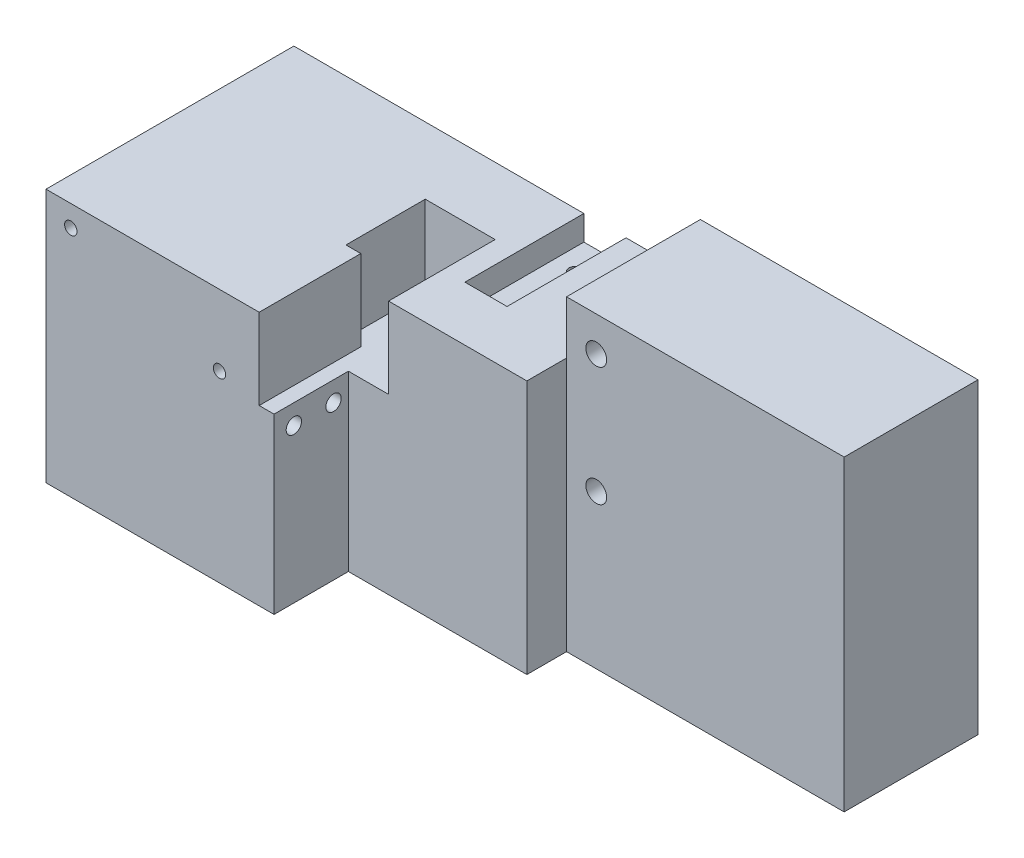
SolidWorks part; units mm, degrees
material "MC nylon"
ref_plane "Front Plane" through (0, 0, 0) normal (0, 0, 1) x (1, 0, 0)
ref_plane "Top Plane" through (0, 0, 0) normal (0, 1, 0) x (1, 0, 0)
ref_plane "Right Plane" through (0, 0, 0) normal (1, 0, 0) x (0, 0, -1)
sketch "Sketch1" plane through (0, 0, 0) normal (0, 1, 0) x (1, 0, 0)
  line L1 (0, 0) -> (138, 0)
  line L2 (0, 0) -> (0, 50)
  line L3 (0, 50) -> (138, 50)
  line L4 (138, 0) -> (138, 50)
  dimension "D1" = 50
  dimension "D2" = 138
extrude "Boss-Extrude1" add sketch "Sketch1" against normal blind 62
sketch "Sketch2" plane through (0, 0, 0) normal (0, 0, 1) x (1, 0, 0)
  line L0 (0, -62) -> (0, 0) construction
  line L1 (0, 0) -> (82, 0)
  line L2 (0, 0) -> (0, -8)
  line L3 (0, -8) -> (82, -8)
  line L4 (82, 0) -> (82, -8)
  dimension "D1" = 82
  dimension "D2" = 8
extrude "Cut-Extrude1" cut sketch "Sketch2" against normal through all
sketch "Sketch3" plane through (0, 0, 0) normal (0, 0, 1) x (1, 0, 0)
  line L1 (138, -62) -> (82, -62)
  line L2 (138, -62) -> (138, 0)
  line L3 (138, 0) -> (82, 0)
  line L4 (82, -62) -> (82, 0)
extrude "Cut-Extrude2" cut sketch "Sketch3" against normal blind 23
sketch "Sketch4" plane through (0, -8, 0) normal (0, 1, 0) x (1, 0, 0)
  line L1 (40, 36.5) -> (54.1, 36.5)
  line L2 (40, 36.5) -> (40, 20.5)
  line L3 (43, 0) -> (54.1, 0)
  line L4 (54.1, 36.5) -> (54.1, 0)
  line L9 (0, 0) -> (82, 0) construction
  line L10 (0, 50) -> (0, 0) construction
  line L11 (40, 20.5) -> (43, 20.5)
  line L14 (43, 20.5) -> (43, 0)
  dimension "D1" = 40
  dimension "D2" = 36.5
  dimension "D3" = 14.1
  dimension "D4" = 11.1
  dimension "D5" = 20.5
extrude "Cut-Extrude3" cut sketch "Sketch4" against normal blind 19
sketch "Sketch5" plane through (0, -8, 0) normal (0, 1, 0) x (1, 0, 0)
  line L6 (0, 50) -> (82, 50) construction
  line L7 (82, 0) -> (46, 0)
  line L8 (82, 0) -> (82, 15)
  line L9 (82, 15) -> (46, 15)
  line L10 (46, 0) -> (46, 15)
  dimension "D1" = 35
  dimension "D2" = 36
extrude "Cut-Extrude4" cut sketch "Sketch5" against normal through all
hole_wizard "M3x0.5 Tapped Hole1" positions "Sketch9" profile "Sketch10" tap size "M3x0.5" standard "JIS"
sketch "Sketch9" plane through (0, 0, 0) normal (0, 0, 1) x (1, 0, 0)
  line L0 (0, -8) -> (43, -8) construction
  line L1 (0, -62) -> (0, -8) construction
  point P0 (5, -15)
  point P2 (35, -25)
  dimension "D1" = 7
  dimension "D2" = 5
  dimension "D3" = 30
  dimension "D4" = 10
sketch "Sketch10" plane through (5, -15, 0) normal (1, 0, 0) x (0, -1, 0)
  line L0 (0, 0) -> (0, 13.1511)
  line L1 (0, 13.1511) -> (1.25, 12.4)
  line L2 (1.25, 12.4) -> (1.25, 0)
  line L5 (1.25, 0) -> (0, 0)
  line L10 (0, 13.1511) -> (-1.25, 12.4) construction
  line L11 (0, -6.35) -> (0, 107.95) construction
  dimension "Tap Drill Dia." = 2.5
  dimension "Tap Drill Depth" = 12.4
  dimension "Drill Angle" = 118
cosmetic thread "Hole Thread1" parameters "D1"=6, "D2"=3
cosmetic thread "Hole Thread2" parameters "D1"=6, "D2"=3
hole_wizard "M4x0.7 Tapped Hole1" positions "Sketch11" profile "Sketch12" tap size "M4x0.7" standard "JIS"
sketch "Sketch11" plane through (0, -62, 0) normal (0, -1, 0) x (-1, 0, 0)
  line L0 (-138, 23) -> (-138, 50) construction
  line L1 (0, 50) -> (0, 0) construction
  line L2 (-138, 50) -> (0, 50) construction
  point P0 (-128, 35)
  point P2 (-10, 35)
  dimension "D1" = 10
  dimension "D2" = 10
  dimension "D3" = 15
sketch "Sketch12" plane through (128, -62, -35) normal (1, 0, 0) x (0, 0, -1)
  line L0 (0, 0) -> (0, 11.0914)
  line L1 (0, 11.0914) -> (1.65, 10.1)
  line L2 (1.65, 10.1) -> (1.65, 0)
  line L5 (1.65, 0) -> (0, 0)
  line L10 (0, 11.0914) -> (-1.65, 10.1) construction
  line L11 (0, -6.35) -> (0, 107.95) construction
  dimension "Tap Drill Dia." = 3.3
  dimension "Tap Drill Depth" = 10.1
  dimension "Drill Angle" = 118
cosmetic thread "Hole Thread3" parameters "D1"=8, "D2"=4
cosmetic thread "Hole Thread4" parameters "D1"=8, "D2"=4
hole_wizard "Ø3.1 (3.1) Diameter Hole1" positions "Sketch13" profile "Sketch14" hole size "Ø3.1" standard "JIS"
sketch "Sketch13" plane through (46, 0, 0) normal (1, 0, 0) x (0, 0, -1)
  line L0 (0, -62) -> (0, -27) construction
  line L1 (15, -62) -> (0, -62) construction
  point P0 (4, -31)
  point P2 (12, -31)
  dimension "D1" = 8
  dimension "D2" = 4
  dimension "D3" = 31
sketch "Sketch14" plane through (46, -31, -4) normal (0, 1, 0) x (0, 0, -1)
  line L0 (0, 0) -> (0, 10.9313)
  line L1 (0, 10.9313) -> (1.55, 10)
  line L2 (1.55, 10) -> (1.55, 0)
  line L5 (1.55, 0) -> (0, 0)
  line L10 (0, 10.9313) -> (-1.55, 10) construction
  line L11 (0, -6.35) -> (0, 107.95) construction
  dimension "Hole Dia." = 3.1
  dimension "Hole Depth" = 10
  dimension "Drill Angle" = 118
sketch "Sketch15" plane through (0, 0, 0) normal (0, 0, 1) x (1, 0, 0)
  line L0 (82, -62) -> (82, -8) construction
  line L1 (0, -8) -> (82, -8)
  line L2 (0, -8) -> (0, -10.7)
  line L3 (0, -10.7) -> (82, -10.7)
  line L4 (82, -8) -> (82, -10.7)
  dimension "D1" = 2.7
extrude "Cut-Extrude6" cut sketch "Sketch15" against normal through all
sketch "Sketch16" plane through (0, -10.7, 0) normal (0, 1, 0) x (1, 0, 0)
  line L0 (0, 50) -> (82, 50) construction
  line L1 (58.5, 50) -> (67, 50)
  line L2 (58.5, 50) -> (58.5, 26)
  line L3 (58.5, 26) -> (67, 26)
  line L4 (67, 50) -> (67, 26)
  line L7 (82, 50) -> (82, 23) construction
  dimension "D1" = 24
  dimension "D2" = 8.5
  dimension "D3" = 15
extrude "Cut-Extrude7" cut sketch "Sketch16" against normal blind 5
hole_wizard "M3x0.5 Tapped Hole2" positions "Sketch17" profile "Sketch18" tap size "M3x0.5" standard "JIS"
sketch "Sketch17" plane through (0, -15.7, 0) normal (0, 1, 0) x (1, 0, 0)
  line L0 (67, 50) -> (58.5, 50) construction
  line L1 (67, 26) -> (67, 50) construction
  point P0 (62.75, 44)
  dimension "D1" = 6
  dimension "D2" = 4.25
sketch "Sketch18" plane through (62.75, -15.7, -44) normal (1, 0, 0) x (0, 0, 1)
  line L0 (0, 0) -> (0, 8.2511)
  line L1 (0, 8.2511) -> (1.25, 7.5)
  line L2 (1.25, 7.5) -> (1.25, 0)
  line L5 (1.25, 0) -> (0, 0)
  line L10 (0, 8.2511) -> (-1.25, 7.5) construction
  line L11 (0, -6.35) -> (0, 107.95) construction
  dimension "Tap Drill Dia." = 2.5
  dimension "Tap Drill Depth" = 7.5
  dimension "Drill Angle" = 118
cosmetic thread "Hole Thread5" parameters "D1"=6, "D2"=3
hole_wizard "M5x0.8 Tapped Hole1" positions "Sketch21" profile "Sketch22" tap size "M5x0.8" standard "JIS"
sketch "Sketch21" plane through (0, 0, -23) normal (0, 0, 1) x (1, 0, 0)
  line L0 (138, 0) -> (82, 0) construction
  line L1 (82, 0) -> (82, -10.7) construction
  point P0 (88, -7)
  point P2 (88, -31)
  dimension "D1" = 7
  dimension "D2" = 24
  dimension "D3" = 6
sketch "Sketch22" plane through (88, -7, -23) normal (1, 0, 0) x (0, -1, 0)
  line L0 (0, 0) -> (0, 13.6618)
  line L1 (0, 13.6618) -> (2.1, 12.4)
  line L2 (2.1, 12.4) -> (2.1, 0)
  line L5 (2.1, 0) -> (0, 0)
  line L10 (0, 13.6618) -> (-2.1, 12.4) construction
  line L11 (0, -6.35) -> (0, 107.95) construction
  dimension "Tap Drill Dia." = 4.2
  dimension "Tap Drill Depth" = 12.4
  dimension "Drill Angle" = 118
cosmetic thread "Hole Thread8" parameters "D1"=10, "D2"=5
cosmetic thread "Hole Thread9" parameters "D1"=10, "D2"=5
